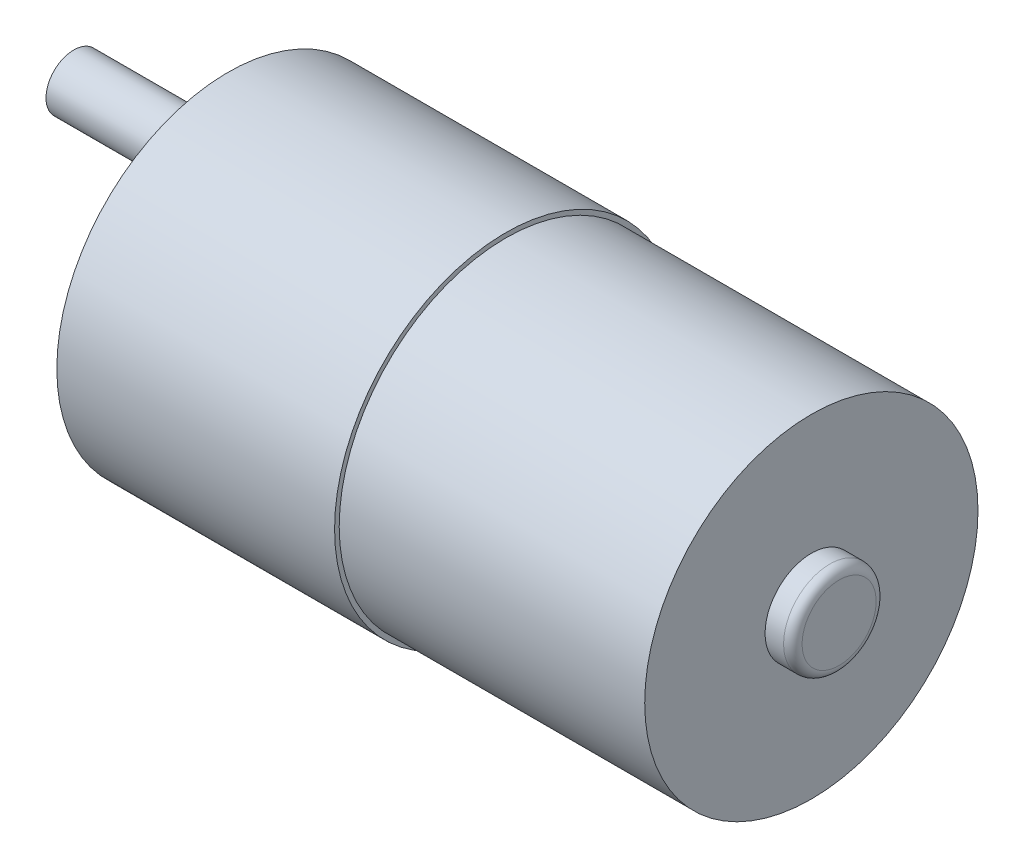
SolidWorks part; units mm, degrees
ref_plane "前视基准面" through (0, 0, 0) normal (0, 0, 1) x (1, 0, 0)
ref_plane "上视基准面" through (0, 0, 0) normal (0, 1, 0) x (1, 0, 0)
ref_plane "右视基准面" through (0, 0, 0) normal (1, 0, 0) x (0, 0, -1)
other "Configuration Table"
sketch "草图1" plane through (0, 0, 0) normal (0, 0, 1) x (1, 0, 0)
  line L0 (-39.7143, 0) -> (39.7143, 0) construction
  line L1 (0, 25.2143) -> (0, -25.3571) construction
  line L2 (0, 0) -> (0, 18)
  line L3 (0, 18) -> (33, 18)
  line L4 (33, 18) -> (33, 0)
  line L5 (33, 0) -> (0, 0)
  line L6 (0, 18.5) -> (-30, 18.5)
  line L7 (-30, 18.5) -> (-30, 0)
  line L8 (-30, 0) -> (0, 0)
  line L9 (0, 18.5) -> (0, 18)
  line L10 (33, 5) -> (35, 5)
  line L11 (36, 4) -> (36, 0)
  line L12 (33, 5) -> (33, 0)
  line L13 (36, 0) -> (33, 0)
  line L14 (-30, 0) -> (0, 0)
  line L15 (0, 18.5) -> (0, 0)
  line L16 (-30, 0) -> (0, 0)
  line L17 (-40.869, 9.25) -> (-30, 9.25) construction
  line L18 (-30, 15.25) -> (-32.6714, 15.25)
  line L19 (-32.6714, 15.25) -> (-32.6714, 9.25)
  line L20 (-32.6714, 12.25) -> (-40.869, 12.25)
  line L21 (-40.869, 12.25) -> (-40.869, 9.25)
  arc A0 (35, 5) -> (36, 4) centre (35, 4) cw
  point P17 (36, 5)
  dimension "D7" = 1
  dimension "D1" = 33
  dimension "D2" = 18
  dimension "D3" = 18.5
  dimension "D4" = 30
  dimension "D5" = 5
  dimension "D6" = 3
  dimension "D8" = 9.25
  dimension "D9" = 6
  dimension "D10" = 12
revolve "旋转1" add sketch "草图1" angle 360 about L0
sketch "草图2" plane through (0, 0, 0) normal (0, 0, 1) x (1, 0, 0)
  line L0 (-30, 15.25) -> (-32.6714, 15.25)
  line L1 (-32.6714, 15.25) -> (-32.6714, 9.25)
  line L2 (-46.6714, 9.25) -> (-32.6714, 9.25)
  line L3 (-46.6714, 9.25) -> (-46.6714, 12.25)
  line L4 (-46.6714, 12.25) -> (-32.6714, 12.25)
  line L5 (-54.7753, 9.25) -> (-27.1357, 9.25) construction
  line L6 (-30, 15.25) -> (-30, 9.25)
  line L8 (-30, 9.25) -> (-32.6714, 9.25)
  line L9 (-46.6714, 9.25) -> (-32.6714, 9.25)
  line L10 (-32.6714, 12.25) -> (-32.6714, 9.25)
  line L11 (-46.6714, 12.25) -> (-32.6714, 12.25)
  dimension "D1" = 14
revolve "旋转3" add sketch "草图2" angle 360 about L5
sketch "草图4" plane through (0, 0, 0) normal (1, 0, 0) x (0, 0, -1)
  line L0 (0, 22.1809) -> (0, -21.5773) construction
  circle A0 centre (8, 0.25) radius 1.5
  circle A1 centre (-8, 0.25) radius 1.5
  circle A3 centre (0, 9.25) radius 6 construction
  dimension "D2" = 3
  dimension "D3" = 15
  dimension "D1" = 8
extrude "切除-拉伸1" cut sketch "草图4" along normal blind 1 from surface at -30 starting at face at (-30, 9.25, -6)
